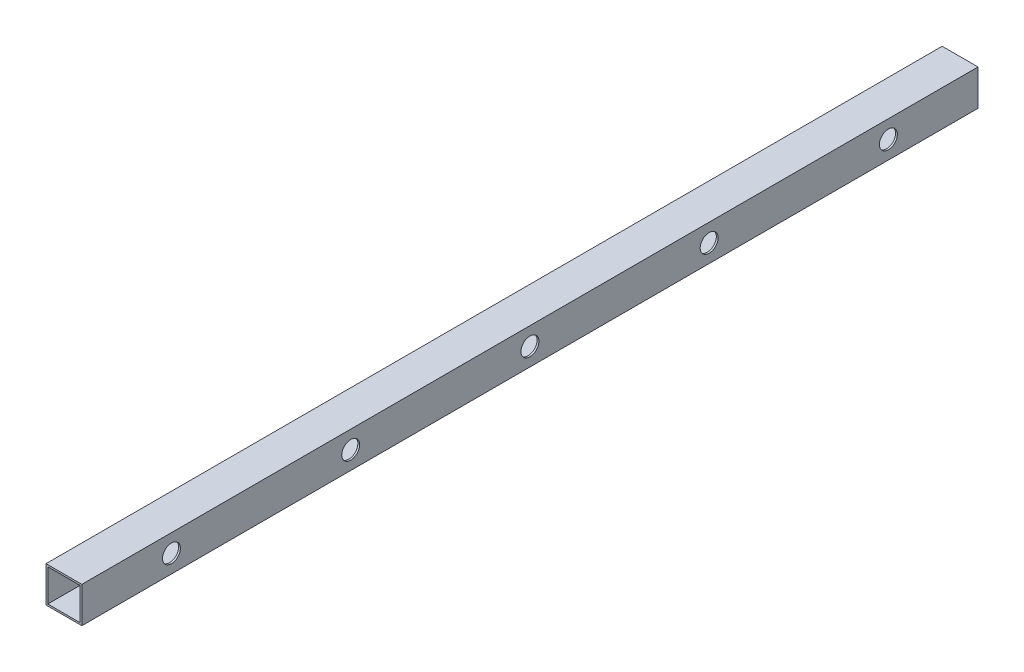
SolidWorks part; units mm, degrees
material "Aleación 1060"
ref_plane "Alzado" through (0, 0, 0) normal (0, 0, 1) x (1, 0, 0)
ref_plane "Planta" through (0, 0, 0) normal (0, 1, 0) x (1, 0, 0)
ref_plane "Vista lateral" through (0, 0, 0) normal (1, 0, 0) x (0, 0, -1)
sketch "Croquis1" plane through (0, 0, 0) normal (0, 0, 1) x (1, 0, 0)
  line L1 (20, -20) -> (-20, -20)
  line L2 (20, -20) -> (20, 20)
  line L3 (20, 20) -> (-20, 20)
  line L4 (-20, -20) -> (-20, 20)
  line L5 (20, -20) -> (-20, 20) construction
  line L6 (20, 20) -> (-20, -20) construction
  point P0 (0, 0)
  dimension "D1" = 40
  dimension "D2" = 40
extrude "Extruir-Lámina1" add sketch "Croquis1" along normal blind 1000 thin
sketch "Croquis2" plane through (20, 0, 0) normal (1, 0, 0) x (0, 0, -1)
  line L0 (-1000, 0) -> (0, 0) construction
  line L1 (-1000, -20) -> (-1000, 20) construction
  line L2 (-500, 0) -> (-500, 20) construction
  line L3 (-1000, 20) -> (0, 20) construction
  circle A0 centre (-500, 0) radius 10
  circle A1 centre (-300, 0) radius 10
  circle A2 centre (-100, 0) radius 10
  circle A3 centre (-700, 0) radius 10
  circle A4 centre (-900, 0) radius 10
  dimension "D1" = 20
extrude "Extruir1" cut sketch "Croquis2" against normal blind 10
sketch "Croquis3" plane through (-20, 0, 0) normal (-1, 0, 0) x (0, 0, 1)
  line L1 (130, -15) -> (70, -15)
  line L2 (130, -15) -> (130, 15)
  line L3 (130, 15) -> (70, 15)
  line L4 (70, -15) -> (70, 15)
  line L5 (130, -15) -> (70, 15) construction
  line L6 (130, 15) -> (70, -15) construction
  line L7 (330, -15) -> (270, -15)
  line L8 (330, -15) -> (330, 15)
  line L9 (330, 15) -> (270, 15)
  line L10 (270, -15) -> (270, 15)
  line L11 (330, -15) -> (270, 15) construction
  line L12 (330, 15) -> (270, -15) construction
  line L13 (530, -15) -> (470, -15)
  line L14 (530, -15) -> (530, 15)
  line L15 (530, 15) -> (470, 15)
  line L16 (470, -15) -> (470, 15)
  line L17 (530, -15) -> (470, 15) construction
  line L18 (530, 15) -> (470, -15) construction
  line L19 (730, -15) -> (670, -15)
  line L20 (730, -15) -> (730, 15)
  line L21 (730, 15) -> (670, 15)
  line L22 (670, -15) -> (670, 15)
  line L23 (730, -15) -> (670, 15) construction
  line L24 (730, 15) -> (670, -15) construction
  line L25 (930, -15) -> (870, -15)
  line L26 (930, -15) -> (930, 15)
  line L27 (930, 15) -> (870, 15)
  line L28 (870, -15) -> (870, 15)
  line L29 (930, -15) -> (870, 15) construction
  line L30 (930, 15) -> (870, -15) construction
  circle A5 centre (900, 0) radius 10 construction
  circle A6 centre (700, 0) radius 10 construction
  circle A7 centre (500, 0) radius 10 construction
  circle A8 centre (300, 0) radius 10 construction
  circle A9 centre (100, 0) radius 10 construction
  circle A10 centre (900, 0) radius 10 construction
  circle A11 centre (700, 0) radius 10 construction
  circle A12 centre (500, 0) radius 10 construction
  circle A13 centre (300, 0) radius 10 construction
  circle A14 centre (100, 0) radius 10 construction
  dimension "D1" = 30
  dimension "D2" = 60
  dimension "D3" = 30
  dimension "D4" = 60
  dimension "D5" = 30
  dimension "D6" = 60
  dimension "D7" = 30
  dimension "D8" = 60
  dimension "D9" = 30
  dimension "D10" = 60
extrude "Extruir2" cut sketch "Croquis3" against normal blind 10
